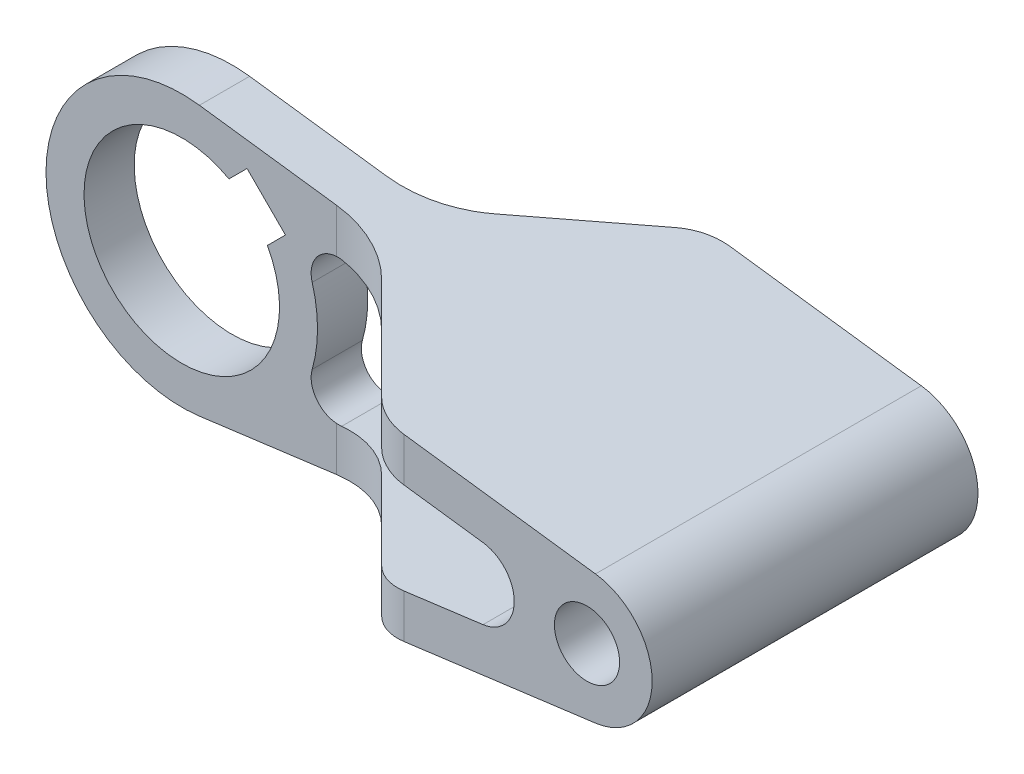
SolidWorks part; units mm, degrees
ref_plane "Front Plane" through (0, 0, 0) normal (0, 0, 1) x (1, 0, 0)
ref_plane "Top Plane" through (0, 0, 0) normal (0, 1, 0) x (1, 0, 0)
ref_plane "Right Plane" through (0, 0, 0) normal (1, 0, 0) x (0, 0, -1)
sketch "Sketch1" plane through (0, 0, 0) normal (0, 0, 1) x (1, 0, 0)
  line L0 (-57.5069, 0) -> (30.4931, 0) construction
  line L1 (-54.2569, 24.7878) -> (44.0531, 11.8982)
  line L2 (-54.2569, -24.7878) -> (44.0531, -11.8982)
  line L3 (-57.5069, 0) -> (-23.659, 33.8479) construction
  line L4 (-48.8155, 15.7626) -> (-45.4861, 19.0919)
  line L5 (-28.0348, 13.2813) -> (23.3511, 6.544)
  line L6 (-45.4861, 19.0919) -> (-38.4151, 12.0208)
  line L7 (-28.0348, -13.2813) -> (23.3511, -6.544)
  line L8 (-38.4151, 12.0208) -> (-41.7444, 8.6915)
  line L9 (-57.5069, 47.3024) -> (-57.5069, -53.786) construction
  arc A0 (-54.2569, 24.7878) -> (-54.2569, -24.7878) centre (-57.5069, 0) ccw
  arc A1 (-48.8155, 15.7626) -> (-41.7444, 8.6915) centre (-57.5069, 0) ccw
  circle A2 centre (42.4931, 0) radius 12
  circle A3 centre (42.4931, 0) radius 6
  arc A4 (23.3511, -6.544) -> (23.3511, 6.544) centre (22.4931, 0) ccw
  arc A5 (-33.4885, -6.9365) -> (-33.4885, 6.9365) centre (-57.5069, 0) ccw
  arc A6 (-28.0348, -13.2813) -> (-33.4885, -6.9365) centre (-28.6848, -8.3238) cw
  arc A7 (-33.4885, 6.9365) -> (-28.0348, 13.2813) centre (-28.6848, 8.3238) cw
  point P22 (-37.1222, -14.4728)
  point P25 (-37.1222, 14.4728)
  dimension "D1" = 50
  dimension "D2" = 36
  dimension "D3" = 12
  dimension "D4" = 24
  dimension "D8" = 20
  dimension "D10" = 6.6
  dimension "D13" = 5
  dimension "D5" = 100
  dimension "D6" = 45
  dimension "D7" = 22
  dimension "D9" = 10
  dimension "D11" = 22.4931
  dimension "D12" = 23.3511
extrude "Boss-Extrude1" add sketch "Sketch1" along normal mid plane 60 contours A2 L1 A0 L2 A1 L4 L6 L8 A5 A7 L5 A4 L7 A6 | A2 A3
sketch "Sketch5" plane through (0, 0, 0) normal (0, 1, 0) x (1, 0, 0)
  line L0 (-82.5069, 0) -> (54.4931, 0) construction
  line L1 (-82.5069, 30) -> (-82.5069, -30) construction
  line L2 (54.4931, -30) -> (54.4931, 30) construction
  line L3 (-82.5069, -4.6215) -> (-28.9834, -4.6215)
  line L4 (-14.8413, -10.4794) -> (4.6793, -30)
  line L5 (-54.2569, -30) -> (44.0531, -30) construction
  line L6 (4.6793, -30) -> (-82.5069, -30)
  line L7 (-82.5069, -30) -> (-54.2569, -30) construction
  line L8 (-82.5069, -30) -> (-82.5069, -4.6215)
  line L9 (-82.5069, 30) -> (-82.5069, 4.6215)
  line L10 (4.6793, 30) -> (-82.5069, 30)
  line L11 (-14.8413, 10.4794) -> (4.6793, 30)
  line L12 (-82.5069, 4.6215) -> (-28.9834, 4.6215)
  line L13 (54.4931, 22) -> (12.1352, 22)
  line L14 (5.0641, 19.0711) -> (-6.9359, 7.0711)
  line L15 (-6.9359, -7.0711) -> (5.0641, -19.0711)
  line L16 (12.1352, -22) -> (54.0314, -22)
  line L17 (4.6793, 30) -> (54.4931, 30) construction
  line L18 (54.4931, 30) -> (44.0531, 30) construction
  line L19 (4.6793, -30) -> (56.5256, -30) construction
  arc A0 (-28.9834, -4.6215) -> (-14.8413, -10.4794) centre (-28.9834, -24.6215) cw
  arc A1 (-14.8413, 10.4794) -> (-28.9834, 4.6215) centre (-28.9834, 24.6215) cw
  arc A2 (5.0641, -19.0711) -> (12.1352, -22) centre (12.1352, -12) ccw
  arc A3 (-6.9359, 7.0711) -> (-6.9359, -7.0711) centre (0.1352, 0) ccw
  arc A4 (12.1352, 22) -> (5.0641, 19.0711) centre (12.1352, 12) ccw
  point P20 (-5.081, -20.2397)
  point P30 (-20.6992, -4.6215)
  point P33 (-20.6992, 4.6215)
  point P38 (-14.0069, 0)
  dimension "D5" = 20
  dimension "D6" = 10
  dimension "D1" = 8
  dimension "D2" = 8
  dimension "D3" = 8
  dimension "D4" = 8
extrude "Cut-Extrude1" cut sketch "Sketch5" against normal mid plane 60 contours A1 L11 L10 L9 L12 | A0 L3 L8 L6 L4
fillet "Fillet1" radius 10 4 edges at (4.6793, -13.0263, -30) (4.6793, 13.0263, -30) (4.6793, -13.0263, 30) (4.6793, 13.0263, 30)
